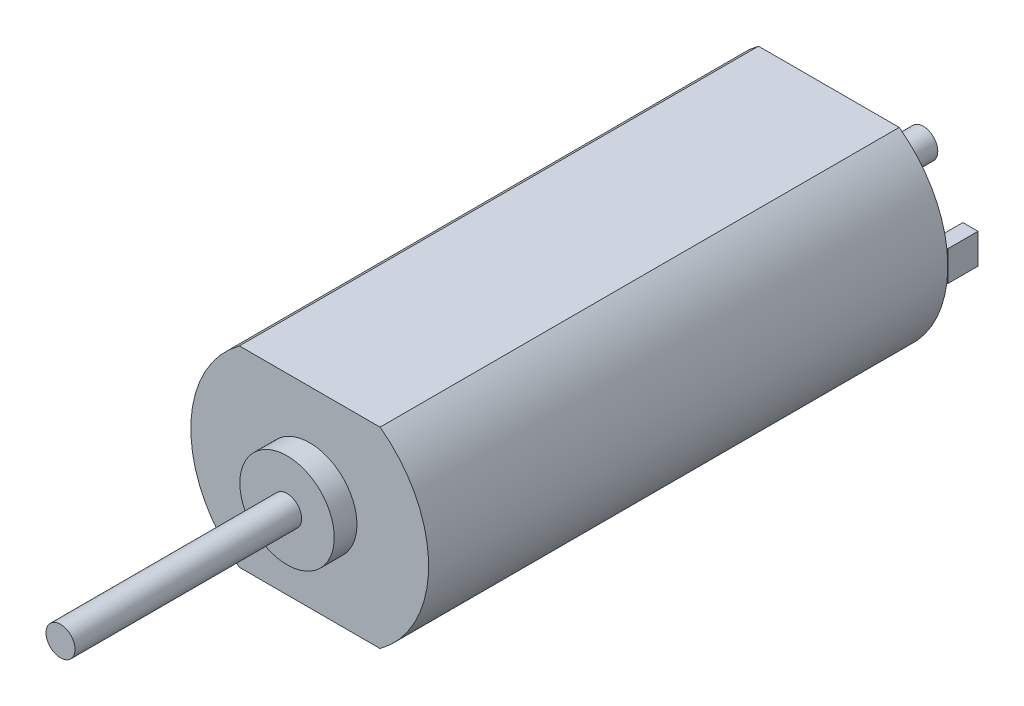
SolidWorks part; units mm, degrees
ref_plane "Front Plane" through (0, 0, 0) normal (0, 0, 1) x (1, 0, 0)
ref_plane "Top Plane" through (0, 0, 0) normal (0, 1, 0) x (1, 0, 0)
ref_plane "Right Plane" through (0, 0, 0) normal (1, 0, 0) x (0, 0, -1)
sketch "Sketch1" plane through (0, 0, 0) normal (0, 0, 1) x (1, 0, 0)
  line L0 (-4.7326, 6.45) -> (4.7326, 6.45)
  line L1 (4.7326, -6.45) -> (-4.7326, -6.45)
  circle A0 centre (0, 0) radius 8
  dimension "D1" = 12.9
  dimension "D2" = 16
extrude "Boss-Extrude1" add sketch "Sketch1" along normal blind 34.925 contours L0 A0 L1
sketch "Sketch2" plane through (0, 0, 34.925) normal (0, 0, 1) x (1, 0, 0)
  circle A0 centre (0, 0) radius 3.175
  dimension "D1" = 6.35
extrude "Boss-Extrude2" add sketch "Sketch2" along normal blind 1.524
sketch "Sketch3" plane through (0, 0, 36.449) normal (0, 0, 1) x (1, 0, 0)
  circle A0 centre (0, 0) radius 0.9779
  dimension "D1" = 1.9558
extrude "Boss-Extrude3" add sketch "Sketch3" along normal blind 15.24
sketch "Sketch4" plane through (0, 0, 0) normal (0, 0, -1) x (-1, 0, 0)
  circle A0 centre (0, 0) radius 0.9779
  circle A1 centre (0, 0) radius 0.9779 construction
extrude "Boss-Extrude4" add sketch "Sketch4" along normal blind 6.35
sketch "Sketch5" plane through (0, 0, 0) normal (0, 0, -1) x (-1, 0, 0)
  line L0 (-6.985, 0) -> (6.985, 0) construction
  line L1 (-8.001, 1.016) -> (-6.985, 1.016)
  line L2 (-8.001, 1.016) -> (-8.001, -1.016)
  line L3 (-8.001, -1.016) -> (-6.985, -1.016)
  line L4 (-6.985, 1.016) -> (-6.985, -1.016)
  line L5 (6.985, 1.016) -> (8.001, 1.016)
  line L6 (6.985, 1.016) -> (6.985, -1.016)
  line L7 (6.985, -1.016) -> (8.001, -1.016)
  line L8 (8.001, 1.016) -> (8.001, -1.016)
  dimension "D1" = 2.032
  dimension "D2" = 1.016
  dimension "D3" = 13.97
extrude "Boss-Extrude5" add sketch "Sketch5" along normal blind 2.032
